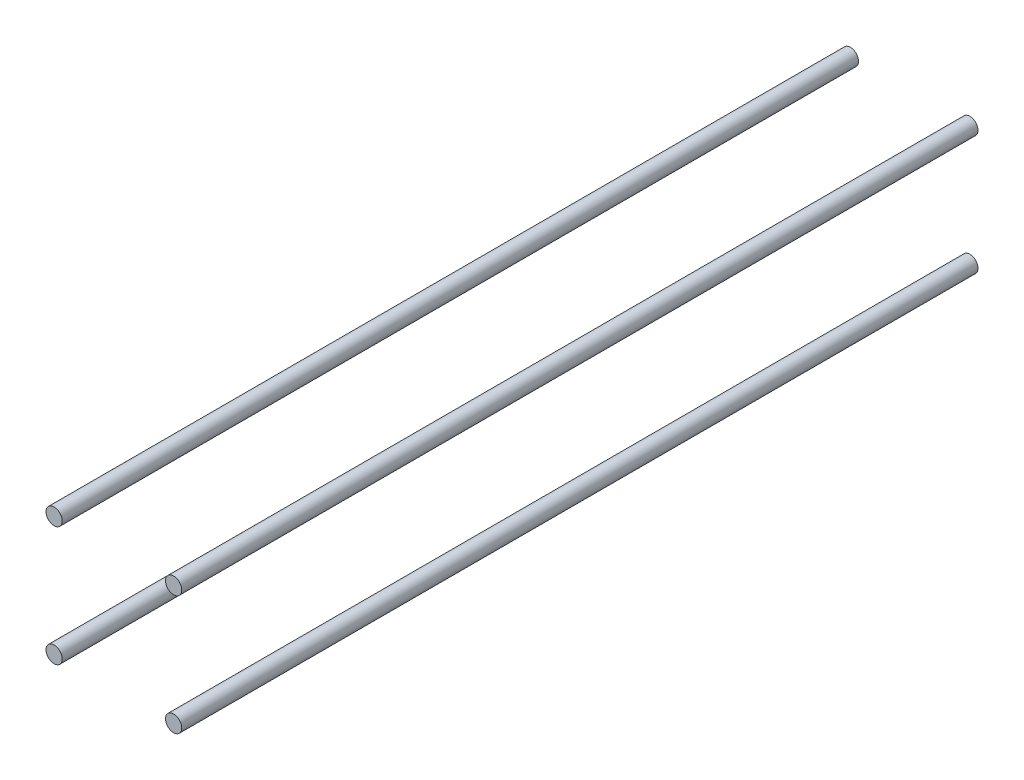
SolidWorks part; units mm, degrees
ref_plane "Спереди" through (0, 0, 0) normal (0, 0, 1) x (1, 0, 0)
ref_plane "Сверху" through (0, 0, 0) normal (0, 1, 0) x (1, 0, 0)
ref_plane "Справа" through (0, 0, 0) normal (1, 0, 0) x (0, 0, -1)
sketch "Эскиз3" plane through (0, 0, 0) normal (0, 0, 1) x (1, 0, 0)
  line L0 (0, 0) -> (35.3298, 0) construction
  line L1 (0, 0) -> (0, 22.7136) construction
  line L2 (0, 0) -> (3080.9055, 3080.9055) construction
  line L3 (0, 0) -> (2447.2076, -2447.2076) construction
  circle A0 centre (0, 0) radius 26 construction
  circle A1 centre (18.3834, 18.3834) radius 2.5
  circle A2 centre (18.3834, -18.3834) radius 2.5
  circle A3 centre (-18.3834, -18.3834) radius 2.5
  circle A4 centre (-18.3834, 18.3834) radius 2.5
  dimension "D3" = 5
  dimension "D4" = 18.3834
  dimension "D5" = 18.3834
  dimension "D6" = 52
  dimension "D7" = 18.3834
  dimension "D1" = 45
  dimension "D2" = 45
  dimension "D8" = 18.3834
extrude "Вытянуть2" add sketch "Эскиз3" along normal blind 245
